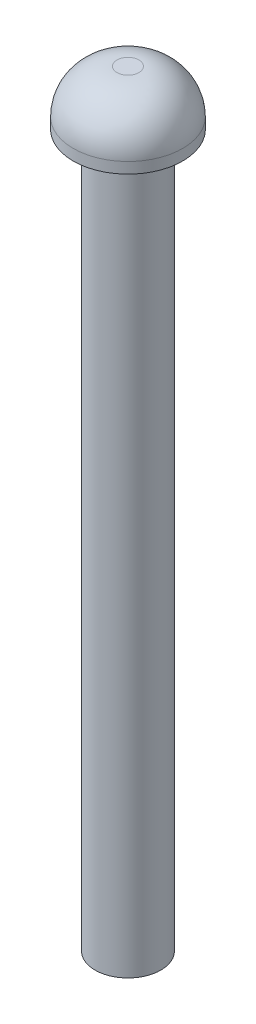
SolidWorks part; units mm, degrees
ref_plane "Plano frontal" through (0, 0, 0) normal (0, 0, 1) x (1, 0, 0)
ref_plane "Plano superior" through (0, 0, 0) normal (0, 1, 0) x (1, 0, 0)
ref_plane "Plano direito" through (0, 0, 0) normal (1, 0, 0) x (0, 0, -1)
sketch "Esboço1" plane through (0, 0, 0) normal (0, 1, 0) x (1, 0, 0)
  circle A0 centre (0, 0) radius 3
extrude "Ressalto-extrusão1" add sketch "Esboço1" along normal blind 65
sketch "Esboço2" plane through (0, 65, 0) normal (0, 1, 0) x (1, 0, 0)
  circle A0 centre (0, 0) radius 5
  dimension "D1" = 10
extrude "Ressalto-extrusão2" add sketch "Esboço2" along normal blind 5
fillet "Filete1" radius 4 1 edges at (0, 70, 5)
